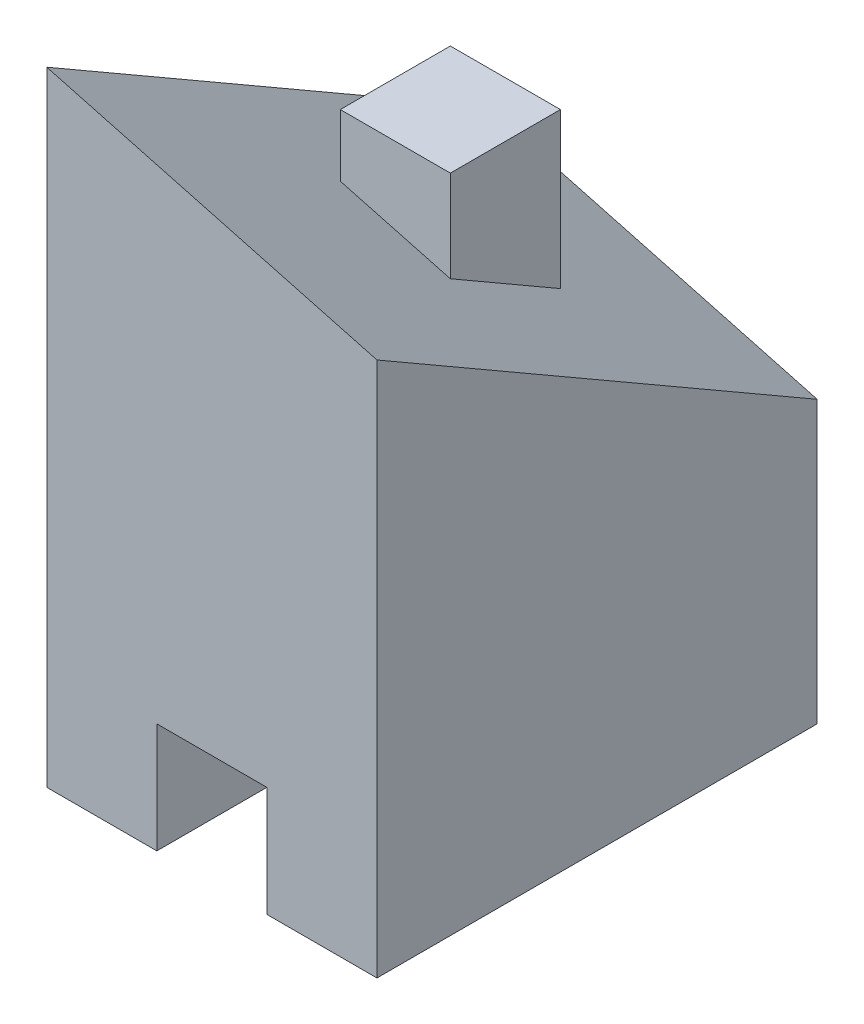
SolidWorks part; units mm, degrees
ref_plane "Plano frontal" through (0, 0, 0) normal (0, 0, 1) x (1, 0, 0)
ref_plane "Plano superior" through (0, 0, 0) normal (0, 1, 0) x (1, 0, 0)
ref_plane "Plano direito" through (0, 0, 0) normal (1, 0, 0) x (0, 0, -1)
sketch "Esboço1" plane through (0, 0, 0) normal (1, 0, 0) x (0, 0, -1)
  line L0 (-60, 0) -> (-60, 85)
  line L1 (-60, 85) -> (0, 85)
  line L2 (0, 85) -> (0, 0)
  line L3 (0, 0) -> (-60, 0)
  dimension "D1" = 85
  dimension "D2" = 60
extrude "Ressalto-extrusão1" add sketch "Esboço1" along normal blind 45
sketch "Esboço3" plane through (0, 0, 60) normal (0, 0, 1) x (1, 0, 0)
  line L0 (0, 85) -> (45, 72.9423)
  line L2 (45, 0) -> (45, 85) construction
  line L3 (45, 0) -> (45, 85) construction
  dimension "D1" = 15
sketch "Esboço4" plane through (45, 0, 0) normal (1, 0, 0) x (0, 0, -1)
  line L0 (-60, 72.9423) -> (0, 38.3013)
  line L1 (-60, 85) -> (-60, 72.9423) construction
  line L2 (-60, 85) -> (-60, 0) construction
  line L3 (0, 0) -> (0, 85) construction
  dimension "D1" = 30
sketch "Esboço5" plane through (0, 0, 0) normal (-1, 0, 0) x (0, 0, 1)
  line L0 (60, 85) -> (0, 50.359)
  line L1 (0, 0) -> (0, 85) construction
  line L2 (60, 72.9423) -> (0, 38.3013) construction
sketch "Esboço6" plane through (0, 0, 0) normal (0, 0, -1) x (-1, 0, 0)
  line L0 (0, 50.359) -> (-45, 38.3013)
  line L1 (0, 85) -> (0, 50.359) construction
  line L2 (-45, 72.9423) -> (-45, 38.3013) construction
  line L3 (0, 0) -> (0, 85) construction
  point P6 (-45, 32.2883)
  point P7 (0, 45.6575)
sketch3d "3DSketch1"
sketch "Esboço7" plane through (9.6031, 35.8394, -20.6919) normal (-0.226, -0.8436, 0.4871) x (-0.9741, 0.1958, -0.113)
  line L4 (24.7777, -100.2959) -> (24.7777, -10.2959)
  line L5 (24.7777, -10.2959) -> (-45.2223, -10.2959)
  line L6 (-45.2223, -10.2959) -> (-45.2223, -100.2959)
  line L7 (-45.2223, -100.2959) -> (24.7777, -100.2959)
  point P0 (24.7777, -11.4962)
  point P3 (18.1709, -12.3964)
  dimension "D1" = 70
  dimension "D2" = 90
  dimension "D3" = 10.2959
  dimension "D4" = 24.7777
extrude "Corte-extrusão1" cut sketch "Esboço7" against normal up to next
sketch3d "3DSketch3" plane through (0, 0, 0) normal (0, 0, 1) x (1, 0, 0)
  dimension "D1" = 75
sketch "Esboço8" plane through (0, 75, 0) normal (0, 1, 0) x (1, 0, 0)
  line L0 (0, -60) -> (45, -60) construction
  line L1 (15, -35) -> (30, -35)
  line L2 (15, -35) -> (15, -20)
  line L3 (15, -20) -> (30, -20)
  line L4 (30, -35) -> (30, -20)
  line L5 (45, -60) -> (45, 0) construction
  dimension "D1" = 15
  dimension "D2" = 15
  dimension "D3" = 25
  dimension "D4" = 15
extrude "Ressalto-extrusão2" add sketch "Esboço8" against normal up to next
sketch "Esboço9" plane through (0, 0, 0) normal (0, 0, -1) x (-1, 0, 0)
  line L0 (-30, 0) -> (-30, 15)
  line L1 (-45, 0) -> (0, 0) construction
  line L2 (-30, 15) -> (-15, 15)
  line L3 (-15, 15) -> (-15, 0)
  line L4 (-15, 0) -> (-30, 0)
  line L5 (-45, 0) -> (-45, 38.3013) construction
  line L6 (0, 0) -> (0, 50.359) construction
  dimension "D1" = 15
  dimension "D2" = 15
  dimension "D3" = 15
extrude "Corte-extrusão2" cut sketch "Esboço9" against normal up to next
